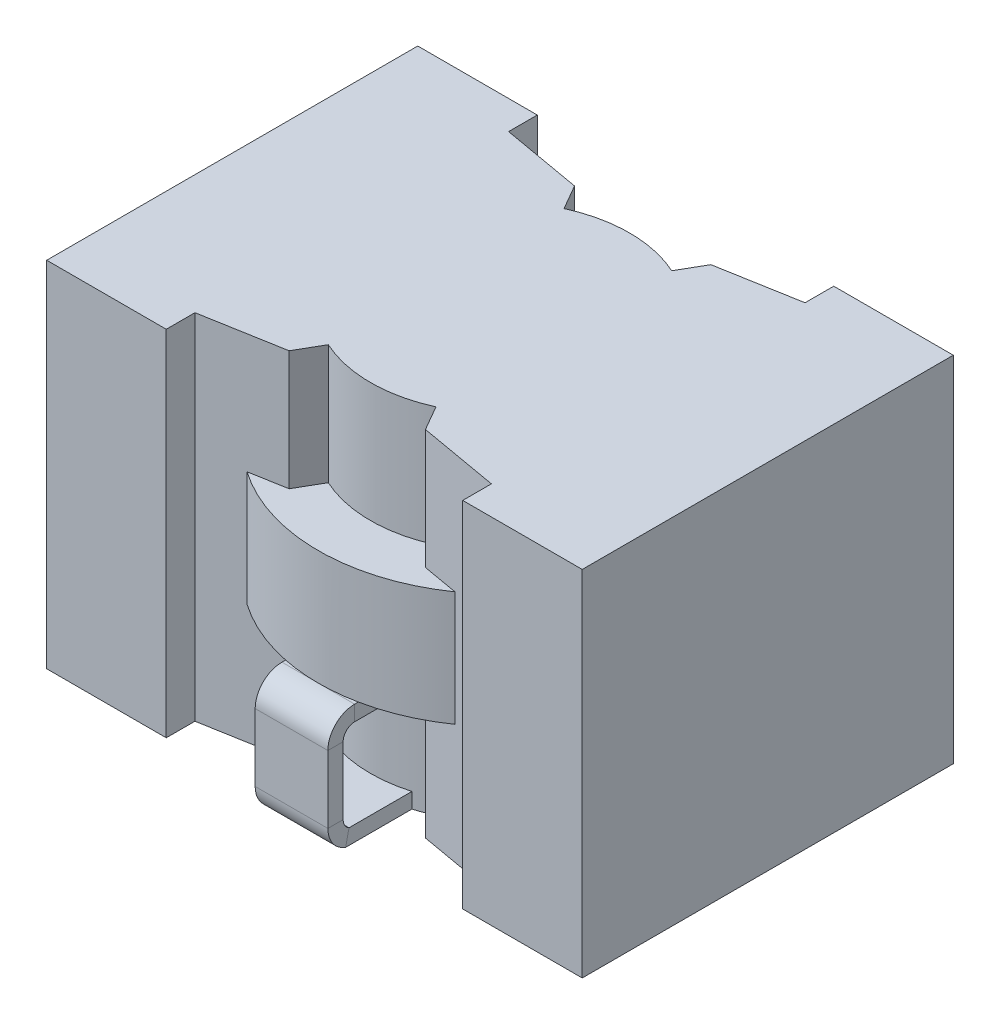
SolidWorks part; units mm, degrees
ref_plane "Front Plane" through (0, 0, 0) normal (0, 0, 1) x (1, 0, 0)
ref_plane "Top Plane" through (0, 0, 0) normal (0, 1, 0) x (1, 0, 0)
ref_plane "Right Plane" through (0, 0, 0) normal (1, 0, 0) x (0, 0, -1)
sketch "Sketch1" plane through (0, 0, 0) normal (0, 1, 0) x (1, 0, 0)
  line L1 (0, 0) -> (28, 0)
  line L2 (0, 0) -> (0, 19.4)
  line L3 (0, 19.4) -> (28, 19.4)
  line L4 (28, 0) -> (28, 19.4)
  dimension "D1" = 19.4
  dimension "D2" = 28
extrude "Boss-Extrude1" add sketch "Sketch1" along normal blind 18.5
sketch "Sketch2" plane through (0, 18.5, 0) normal (0, 1, 0) x (1, 0, 0)
  line L0 (0, 19.4) -> (6.25, 19.4) construction
  line L1 (28, 19.4) -> (0, 19.4) construction
  line L2 (6.25, 19.4) -> (6.25, 17.9)
  line L3 (6.25, 17.9) -> (10.4354, 17.162)
  line L4 (10.4354, 17.162) -> (11.1854, 15.863)
  line L5 (28, 19.4) -> (21.75, 19.4) construction
  line L6 (21.75, 19.4) -> (21.75, 17.9)
  line L7 (21.75, 17.9) -> (17.5646, 17.162)
  line L8 (17.5646, 17.162) -> (16.8146, 15.863)
  line L9 (10.4354, 17.162) -> (17.5646, 17.162) construction
  line L10 (11.1854, 15.863) -> (16.8146, 15.863) construction
  line L11 (0, 9.7) -> (28, 9.7) construction
  line L12 (0, 19.4) -> (0, 0) construction
  line L13 (28, 0) -> (28, 19.4) construction
  line L14 (6.25, 19.4) -> (21.75, 19.4)
  arc A0 (11.1854, 15.863) -> (16.8146, 15.863) centre (14, 9.7) cw
  line M16 (28, 19.4) -> (0, 19.4)
  dimension "D1" = 6.25
  dimension "D2" = 1.5
  dimension "D3" = 4.25
  dimension "D4" = 1.5
  dimension "D5" = 10
  dimension "D6" = 30
extrude "Cut-Extrude1" cut sketch "Sketch2" against normal up to next contours L4 A0 L8 L7 L6 L2 L3 M16
ref_plane "Plane1" through (0, 0, -9.7) normal (0, 0, 1) x (1, 0, 0)
mirror "Mirror1" about plane through (0, 0, -9.7) normal (0, 0, 1) of "Cut-Extrude1"
ref_plane "Plane2" through (0, 9.25, 0) normal (0, 1, 0) x (1, 0, 0)
sketch "Sketch3" plane through (0, 9.25, 0) normal (0, 1, 0) x (1, 0, 0)
  line L0 (0, 9.7) -> (28, 9.7) construction
  line L1 (0, 19.4) -> (0, 0) construction
  line L2 (28, 0) -> (28, 19.4) construction
  circle A0 centre (14, 9.7) radius 9.5
  dimension "D1" = 19
extrude "Boss-Extrude2" add sketch "Sketch3" along normal mid plane 6
sketch "Sketch4" plane through (0, 0, -9.7) normal (0, 0, 1) x (1, 0, 0)
  line L0 (19.4349, 12.25) -> (8.5651, 12.25) construction
  line L1 (20.6146, 12.25) -> (16.8146, 12.25)
  line L2 (20.6146, 12.25) -> (20.6146, 13.05)
  line L3 (20.6146, 13.05) -> (16.8146, 13.05)
  line L4 (16.8146, 12.25) -> (16.8146, 13.05)
  line L5 (16.8146, 12.25) -> (16.8146, 18.5) construction
  line L6 (18.7146, 13.05) -> (18.7146, 12.25) construction
  dimension "D1" = 0.8
  dimension "D2" = 3.8
ref_plane "Plane3" through (18.7146, 0, 0) normal (-1, 0, 0) x (0, 0, 1)
sketch "Sketch6" plane through (18.7146, 0, 0) normal (-1, 0, 0) x (0, 0, 1)
  line L1 (-9.7, 12.65) -> (-20.9, 12.65)
  line L2 (-9.7, 13.05) -> (-9.7, 12.25) construction
  line L3 (-21.9, 11.65) -> (-21.9, 1.4)
  line L4 (-22.9, 0.4) -> (-26.1, 0.4)
  line L5 (0, 0) -> (-27.1196, 0) construction
  arc A0 (-20.9, 12.65) -> (-21.9, 11.65) centre (-20.9, 11.65) ccw
  arc A1 (-21.9, 1.4) -> (-22.9, 0.4) centre (-22.9, 1.4) cw
  dimension "D3" = 1
  dimension "D4" = 1
  dimension "D1" = 12.2
  dimension "D2" = 4.2
  dimension "D5" = 0.4
sweep "Sweep1" add profiles "Sketch4" path "Sketch6"
sketch "Sketch7" plane through (0, 0, -9.7) normal (0, 0, 1) x (1, 0, 0)
  line L1 (11.1854, 6.25) -> (7.3854, 6.25)
  line L2 (11.1854, 6.25) -> (11.1854, 5.45)
  line L3 (11.1854, 5.45) -> (7.3854, 5.45)
  line L4 (7.3854, 6.25) -> (7.3854, 5.45)
  line L5 (11.1854, 12.25) -> (11.1854, 18.5) construction
  line L7 (11.1854, 6.25) -> (10.4354, 6.25) construction
  line L8 (9.2854, 6.25) -> (9.2854, 5.45) construction
  dimension "D1" = 3.8
  dimension "D2" = 0.8
ref_plane "Plane4" through (9.2854, 0, 0) normal (-1, 0, 0) x (0, 0, 1)
sketch "Sketch8" plane through (9.2854, 0, 0) normal (-1, 0, 0) x (0, 0, 1)
  line L0 (-9.7, 5.85) -> (-20.9, 5.85)
  line L1 (-9.7, 6.25) -> (-9.7, 5.45) construction
  line L2 (-21.9, 4.85) -> (-21.9, 1.4)
  line L3 (-22.9, 0.4) -> (-26.1, 0.4)
  line L4 (0, 0) -> (-27.8953, 0) construction
  arc A0 (-20.9, 5.85) -> (-21.9, 4.85) centre (-20.9, 4.85) ccw
  arc A1 (-21.9, 1.4) -> (-22.9, 0.4) centre (-22.9, 1.4) cw
  dimension "D1" = 1
  dimension "D2" = 1
  dimension "D3" = 4.2
  dimension "D4" = 12.2
  dimension "D5" = 0.4
sweep "Sweep2" add profiles "Sketch7" path "Sketch8"
sketch "Sketch9" plane through (0, 0, -9.7) normal (0, 0, 1) x (1, 0, 0)
  line L0 (16.8146, 6.25) -> (17.5646, 6.25) construction
  line L1 (12.1, 6.25) -> (15.9, 6.25)
  line L2 (12.1, 6.25) -> (12.1, 5.45)
  line L3 (12.1, 5.45) -> (15.9, 5.45)
  line L4 (15.9, 6.25) -> (15.9, 5.45)
  line L5 (14, 5.45) -> (14, 0) construction
  line L6 (0, 0) -> (14, 0) construction
  line L7 (14, 5.45) -> (14, 6.25) construction
  dimension "D1" = 0.8
  dimension "D2" = 3.8
  dimension "D3" = 14
ref_plane "Plane5" through (14, 0, 0) normal (-1, 0, 0) x (0, 0, 1)
sketch "Sketch12" plane through (14, 0, 0) normal (-1, 0, 0) x (0, 0, 1)
  line L0 (-9.7, 5.85) -> (-0.2, 5.85)
  line L1 (-9.7, 5.45) -> (-9.7, 6.25) construction
  line L2 (0.8, 4.85) -> (0.8, 1.3225)
  line L3 (0.1859, 0.4) -> (-9.7, 0.4)
  line L4 (-9.7, 5.45) -> (-9.7, 0) construction
  arc A0 (-0.2, 5.85) -> (0.8, 4.85) centre (-0.2, 4.85) cw
  arc A1 (0.8, 1.3225) -> (0.1859, 0.4) centre (-0.2, 1.3225) cw
  dimension "D2" = 1
  dimension "D3" = 1
  dimension "D1" = 0.4
  dimension "D4" = 10.5
sweep "Sweep3" add profiles "Sketch9" path "Sketch12"
